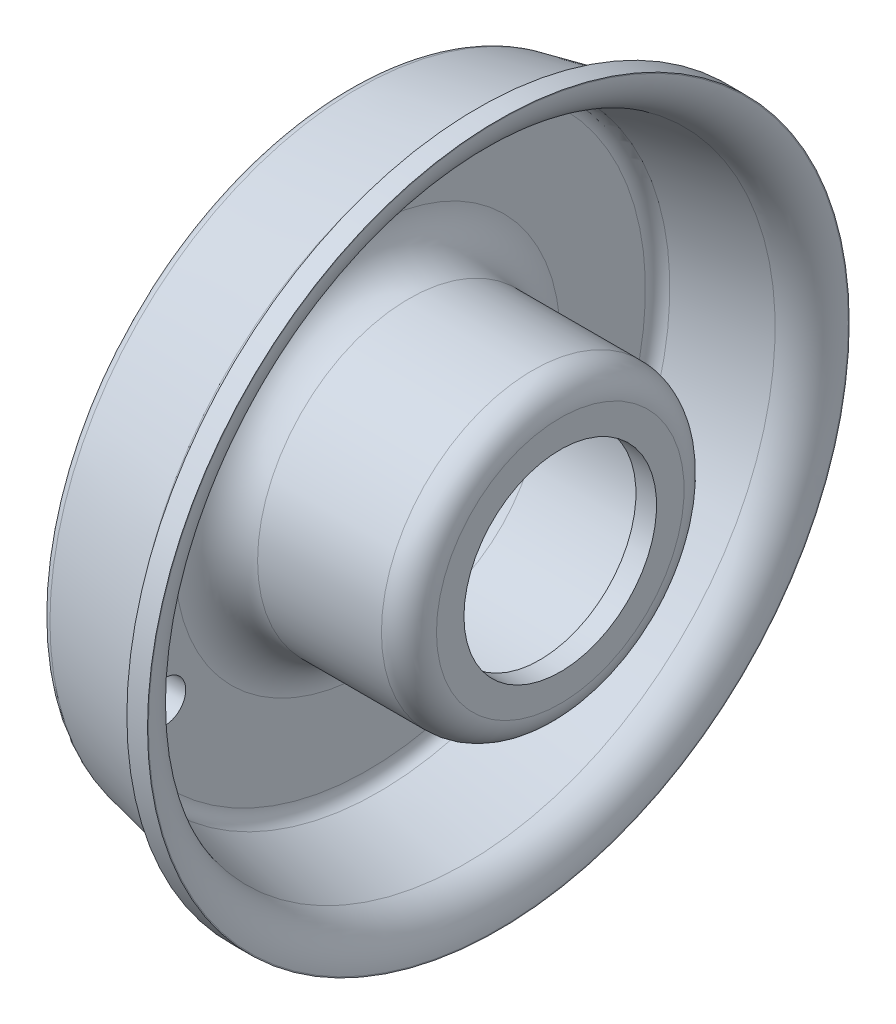
SolidWorks part; units mm, degrees
material "C355.0-T61 Permanent Mold cast (SS)"
ref_plane "Front Plane" through (0, 0, 0) normal (0, 0, 1) x (1, 0, 0)
ref_plane "Top Plane" through (0, 0, 0) normal (0, 1, 0) x (1, 0, 0)
ref_plane "Right Plane" through (0, 0, 0) normal (1, 0, 0) x (0, 0, -1)
sketch "Sketch1" plane through (0, 0, 0) normal (0, 1, 0) x (1, 0, 0)
  line L0 (15.5, 0) -> (31, 0) construction
  line L2 (20, -11) -> (29, -11)
  line L4 (16.294, -22.3842) -> (23.809, -23.9664)
  line L5 (25, -25.4342) -> (25, -25.5)
  line L6 (17.794, -21.1672) -> (24.118, -22.4985)
  line L7 (25, -25.5) -> (26.5, -25.5)
  line L9 (26.5, -25.4342) -> (26.5, -25.5)
  line L11 (31, -7) -> (31, -9)
  line L12 (16.691, -22.4678) -> (25, -24.2171) construction
  line L13 (15.5, -25.5) -> (31, -25.5) construction
  line L14 (26.5, -23) -> (26.5, -33.6659) construction
  line L15 (25, -24.2171) -> (25, -33.6659) construction
  line L16 (17, -21) -> (26.5, -23) construction
  line L17 (20, -9.5) -> (29, -9.5)
  line L18 (29.5, -7) -> (29.5, -9)
  line L19 (29.5, -7) -> (31, -7)
  line L20 (17, -14) -> (17, -20.1886)
  line L23 (15.5, -14) -> (15.5, -21.4057)
  arc A1 (29, -11) -> (31, -9) centre (29, -9) ccw
  arc A2 (17, -14) -> (20, -11) centre (20, -14) cw
  arc A3 (24.118, -22.4985) -> (26.5, -25.4342) centre (23.5, -25.4342) cw
  arc A4 (25, -25.4342) -> (23.809, -23.9664) centre (23.5, -25.4342) ccw
  arc A5 (15.5, -14) -> (20, -9.5) centre (20, -14) cw
  arc A6 (29, -9.5) -> (29.5, -9) centre (29, -9) ccw
  arc A7 (16.294, -22.3842) -> (15.5, -21.4057) centre (16.5, -21.4057) cw
  arc A8 (17.794, -21.1672) -> (17, -20.1886) centre (18, -20.1886) cw
  dimension "D4" = 25.5
  dimension "D12" = 3
  dimension "D6" = 3
  dimension "D7" = 1.5
  dimension "D3" = 1
  dimension "D5" = 1.5
  dimension "D8" = 9.5
  dimension "D9" = 7
  dimension "D10" = 22.3842
  dimension "D2" = 1.5
revolve "Revolve1" add sketch "Sketch1" angle 360 about L0
sketch "Sketch2" plane through (0, 0, 0) normal (1, 0, 0) x (0, 0, -1)
  circle A0 centre (0, 17) radius 1.5
  circle A1 centre (14.7224, -8.5) radius 1.5
  circle A2 centre (-14.7224, -8.5) radius 1.5
  point P9 (0, 0)
  dimension "D2" = 3
  dimension "D1" = 17
  dimension "D3" = 3
extrude "Cut-Extrude2" cut sketch "Sketch2" along normal blind 25
